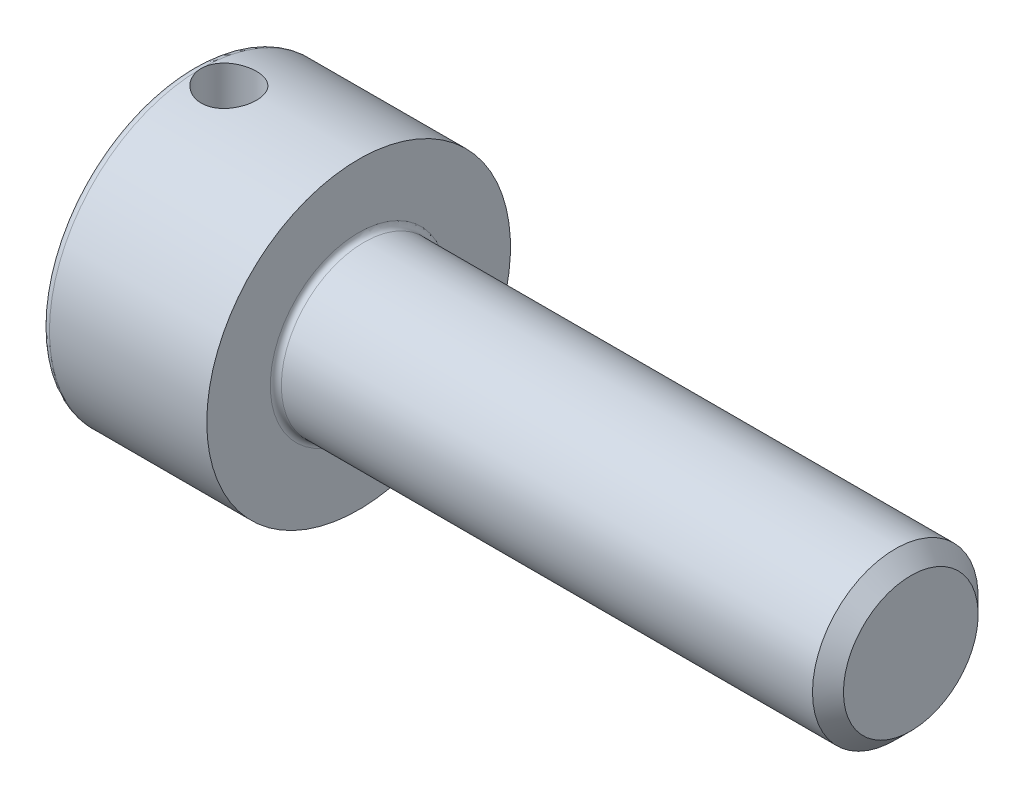
SolidWorks part; units mm, degrees
revolve "Base-Revolve" add sketch "BodySke"
sketch "BodySke" plane through (0, 0, 0) normal (0, 0, 1) x (1, 0, 0)
  line L0 (0, 0) -> (0, 2.75)
  line L1 (0, 2.75) -> (3, 2.75)
  line L2 (3, 2.75) -> (3, 1.5)
  line L3 (3, 1.5) -> (12.7195, 1.5)
  line L4 (13, 1.2195) -> (13, 0)
  line L5 (13, 0) -> (0, 0)
  line L6 (-31.75, 0) -> (127, 0) construction
  line L8 (13, 1.2195) -> (12.7195, 1.5)
  line L10 (13, -1.2195) -> (12.7195, -1.5) construction
  line L11 (3.5, 9.525) -> (3.5, 3.175) construction
  line L12 (3, 9.525) -> (3, 3.175) construction
  line L13 (-47, 9.525) -> (-47, 3.175) construction
  dimension "Head_ht" = 3
  dimension "Length" = 10
  dimension "Body_ch_ang" = 45
  dimension "Diameter" = 3
  dimension "Minor_dia" = 2.439
  dimension "Advance" = 0.5
  dimension "Thread_nom" = 10
  dimension "Thread_length" = 60
  dimension "Head_dia" = 5.5
cosmetic thread "ThreadCosmetic" [suppressed]
fillet "Fillet1" radius 0.1 1 edges at (3, 0, 1.5)
fillet "Fillet2" radius 0.15 1 edges at (0, 0, 2.75)
ref_plane "Plane1" through (0, 0, 0) normal (0, 0, 1) x (1, 0, 0)
ref_plane "Plane2" through (0, 0, 0) normal (0, 1, 0) x (1, 0, 0)
ref_plane "Plane3" through (0, 0, 0) normal (1, 0, 0) x (0, 0, -1)
sketch "Sketch2" plane through (0, 0, 0) normal (0, 0, 1) x (1, 0, 0)
  line L0 (0, 1.28) -> (1.3, 1.28)
  line L1 (1.3, 1.28) -> (2.039, 0)
  line L2 (-31.75, 0) -> (127, 0) construction
  line L3 (2.039, 0) -> (0, 0)
  line L4 (0, 0) -> (0, 1.28)
  line L6 (0, 0) -> (47.625, 0) construction
  dimension "D1" = 1.28
  dimension "D2" = 60
  dimension "Depth" = 1.3
revolve "Hex-PreBroach" cut sketch "Sketch2" angle 360 about L6
sketch "Sketch3" plane through (0, 0, 0) normal (-1, 0, 0) x (0, 0.5, 0.866)
  line L0 (0.739, 1.28) -> (-0.739, 1.28)
  line L1 (-0.739, 1.28) -> (-1.478, 0)
  line L2 (0.739, 1.28) -> (1.478, 0)
  line L3 (0.739, -1.28) -> (1.478, 0)
  line L4 (0.739, -1.28) -> (-0.739, -1.28)
  line L5 (-0.739, -1.28) -> (-1.478, 0)
  dimension "D1" = 1.28
  dimension "D2" = 1.28
  dimension "Hex_size" = 2.56
extrude "Hex" cut sketch "Sketch3" against normal blind 1.3
sketch "ThdSchSke" plane through (0, 0, 0) normal (0, 0, 1) x (1, 0, 0)
  line L0 (4.5, -1.2195) -> (4.3036, -1.5)
  line L1 (4.5, -1.2195) -> (4.6964, -1.5)
  line L2 (4.6964, -1.5) -> (4.6964, -1.875)
  line L3 (-3.175, 0) -> (5.1513, 0) construction
  line L4 (0, 2.6) -> (0, -2.6) construction
  line L5 (4.6964, -1.875) -> (4.3036, -1.875)
  line L6 (4.3036, -1.875) -> (4.3036, -1.5)
  dimension "Thread_minor" = 2.439
  dimension "Diameter" = 3
  dimension "Start" = 4.5
revolve "ThreadSchematic" [suppressed] cut sketch "ThdSchSke" angle 360 about L3
pattern_linear "ThdSchPat" [suppressed]
sketch "Sketch4" plane through (0, 0, 0) normal (0, 1, 0) x (1, 0, 0)
  line L0 (0.15, -2.75) -> (0.15, 2.75) construction
  circle A0 centre (0.65, 0) radius 0.5
  dimension "D1" = 0.5
extrude "Cut-Extrude1" cut sketch "Sketch4" against normal through all and the other way through all
equation "\"D2@Sketch3\" = \"Hex_size@Sketch3\" / 2"
equation "\"D1@Sketch3\" = \"Hex_size@Sketch3\" / 2"
equation "\"D1@Sketch2\" = \"Hex_size@Sketch3\" / 2"
equation "\"Thread_minor@ThreadCosmetic\"  =  \"Minor_dia@BodySke\""
equation "\"Depth@Sketch2\" =  \"Key_eng@Hex\""
equation "\"Thread_length@ThreadCosmetic\" = ((sgn( (\"Length@BodySke\" - \"Advance@BodySke\" * 3.0) - \"Thread_nom@BodySke\" )-1)*( (\"Length@BodySke\" - \"Advance@BodySke\" * 3.0) - \"Thread_nom@BodySke\" ))/-2+ \"Thread_nom@BodySke\""
equation "\"Thread_minor@ThdSchSke\" = \"Minor_dia@BodySke\""
equation "\"Diameter@ThdSchSke\" = \"Diameter@BodySke\""
equation "\"Overcut@ThdSchSke\" = \"Diameter@BodySke\" * 1.25"
equation "\"Start@ThdSchSke\" = \"Head_ht@BodySke\" + \"Length@BodySke\" - \"Thread_length@ThreadCosmetic\"  '---Non-countersunk---"
equation "\"Num_threads@ThdSchPat\" = int( \"Thread_length@ThreadCosmetic\" / \"Advance@BodySke\" + 0.999 )  + 1"
equation "\"Advance@ThdSchPat\" = \"Thread_length@ThreadCosmetic\" /  (\"Num_threads@ThdSchPat\" - 1) 'relax it"
equation "\"Num_threads@ThdSchPat\" = \"Num_threads@ThdSchPat\" - sgn( \"Num_threads@ThdSchPat\" - 1) '---chamfered tips only---"
